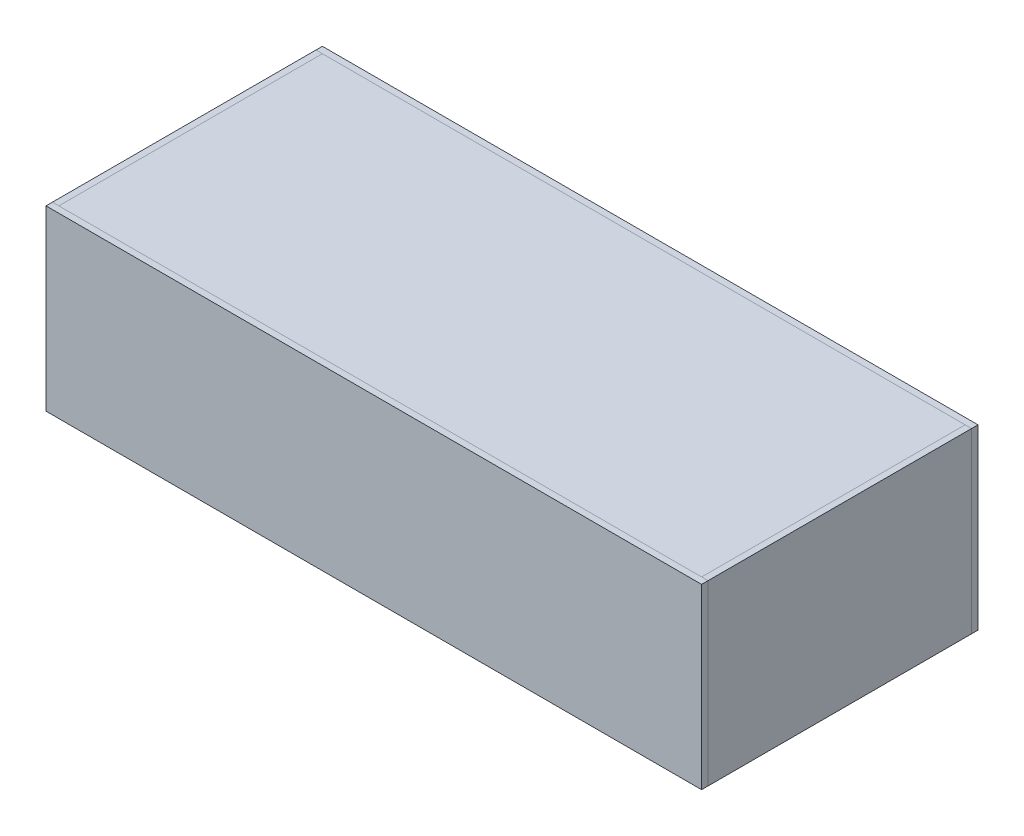
SolidWorks part; units mm, degrees
ref_plane "Plan de face" through (0, 0, 0) normal (0, 0, 1) x (1, 0, 0)
ref_plane "Plan de dessus" through (0, 0, 0) normal (0, 1, 0) x (1, 0, 0)
ref_plane "Plan de droite" through (0, 0, 0) normal (1, 0, 0) x (0, 0, -1)
sketch "Esquisse1" plane through (0, 0, 0) normal (0, 0, 1) x (1, 0, 0)
  line L1 (-714.5758, 139.7008) -> (815.4242, 139.7008)
  line L2 (-714.5758, 139.7008) -> (-714.5758, -275.2992)
  line L3 (-714.5758, -275.2992) -> (815.4242, -275.2992)
  line L4 (815.4242, 139.7008) -> (815.4242, -275.2992)
  dimension "D1" = 1530
  dimension "D2" = 415
extrude "Boss.-Extru.1" add sketch "Esquisse1" along normal blind 15
sketch "Esquisse2" plane through (0, 0, 15) normal (0, 0, 1) x (1, 0, 0)
  line L0 (-699.5758, 139.7008) -> (-699.5758, -275.2992)
  line L1 (815.4242, 139.7008) -> (-714.5758, 139.7008) construction
  line L2 (-714.5758, -275.2992) -> (815.4242, -275.2992) construction
  line L3 (-714.5758, 139.7008) -> (-714.5758, -275.2992) construction
  line L4 (800.4242, -275.2992) -> (800.4242, 139.7008)
  line L5 (815.4242, -275.2992) -> (815.4242, 139.7008) construction
  dimension "D1" = 15
  dimension "D2" = 15
extrude "Extru.-Mince1" add sketch "Esquisse2" along normal blind 615 separate body thin
sketch "Esquisse3" plane through (-699.5758, 0, 0) normal (1, 0, 0) x (0, 0, -1)
  line L0 (-630, 124.7008) -> (-15, 124.7008)
  line L1 (-630, 139.7008) -> (-630, -275.2992) construction
  line L2 (-15, 139.7008) -> (-15, -275.2992) construction
  line L3 (-630, 139.7008) -> (-15, 139.7008) construction
  dimension "D1" = 15
extrude "Extru.-Mince2" add sketch "Esquisse3" along normal blind 1500 separate body thin thin type one direction reverse wall 15
sketch "Esquisse5" plane through (-699.5758, 0, 0) normal (1, 0, 0) x (0, 0, -1)
  line L0 (-165, 24.7008) -> (-180, 24.7008)
  line L2 (-165, 24.7008) -> (-165, 124.7008)
  line L3 (-630, 124.7008) -> (-15, 124.7008) construction
  line L4 (-180, 24.7008) -> (-180, 124.7008)
  line L5 (-180, 124.7008) -> (-165, 124.7008)
  line L6 (-15, 139.7008) -> (-15, -275.2992) construction
  point P0 (-165, 74.7008)
  dimension "D1" = 100
  dimension "D2" = 15
  dimension "D3" = 150
extrude "Boss.-Extru.2" add sketch "Esquisse5" along normal blind 1500 separate body
sketch "Esquisse8" plane through (-699.5758, 0, 0) normal (1, 0, 0) x (0, 0, -1)
  line L5 (-630, 139.7008) -> (-630, -275.2992) construction
  line L6 (-180, 24.7008) -> (-630, 24.7008)
  line L7 (-180, 24.7008) -> (-180, 39.7008)
  line L8 (-180, 39.7008) -> (-630, 39.7008)
  line L9 (-630, 24.7008) -> (-630, 39.7008)
  dimension "D1" = 15
extrude "Boss.-Extru.3" add sketch "Esquisse8" along normal blind 1500 separate body
sketch "Esquisse9" plane through (-699.5758, 0, 0) normal (1, 0, 0) x (0, 0, -1)
  line L1 (-630, -275.2992) -> (-115, -275.2992)
  line L2 (-630, -275.2992) -> (-630, -260.2992)
  line L3 (-630, -260.2992) -> (-115, -260.2992)
  line L4 (-115, -275.2992) -> (-115, -260.2992)
  dimension "D1" = 15
  dimension "D2" = 515
extrude "Boss.-Extru.4" add sketch "Esquisse9" along normal blind 1500 separate body
sketch "Esquisse10" plane through (-699.5758, 0, 0) normal (1, 0, 0) x (0, 0, -1)
  line L5 (-115, -260.2992) -> (-130, -260.2992)
  line L6 (-115, -260.2992) -> (-115, 24.7008)
  line L7 (-115, 24.7008) -> (-130, 24.7008)
  line L8 (-130, -260.2992) -> (-130, 24.7008)
  dimension "D1" = 285
  dimension "D2" = 15
extrude "Boss.-Extru.5" add sketch "Esquisse10" along normal blind 1500 separate body
sketch "Esquisse12" plane through (0, 0, 115) normal (0, 0, -1) x (-1, 0, 0)
  line L0 (-800.4242, -275.2992) -> (699.5758, -275.2992) construction
  line L1 (207.0758, -275.2992) -> (192.0758, -275.2992)
  line L2 (207.0758, -275.2992) -> (207.0758, 24.7008)
  line L3 (207.0758, 24.7008) -> (192.0758, 24.7008)
  line L4 (192.0758, -275.2992) -> (192.0758, 24.7008)
  line L5 (-800.4242, 24.7008) -> (699.5758, 24.7008) construction
  line L6 (699.5758, -260.2992) -> (699.5758, 24.7008) construction
  line L7 (-800.4242, -260.2992) -> (699.5758, -260.2992) construction
  line L8 (-292.9242, -260.2992) -> (-307.9242, -260.2992)
  line L9 (-292.9242, -260.2992) -> (-292.9242, 24.7008)
  line L10 (-292.9242, 24.7008) -> (-307.9242, 24.7008)
  line L11 (-307.9242, -260.2992) -> (-307.9242, 24.7008)
  line L12 (-800.4242, -260.2992) -> (-800.4242, 24.7008) construction
  dimension "D1" = 15
  dimension "D2" = 492.5
  dimension "D3" = 15
  dimension "D4" = 492.5
extrude "Boss.-Extru.6" add sketch "Esquisse12" along normal blind 100 separate body
sketch "Esquisse13" plane through (0, -275.2992, 0) normal (0, -1, 0) x (1, 0, 0)
  line L0 (-699.5758, 630) -> (800.4242, 115) construction
  line L1 (800.4242, 630) -> (-699.5758, 115) construction
  line L2 (-424.5258, 630) -> (-424.5258, 115) construction
  line L3 (800.4242, 630) -> (-699.5758, 630) construction
  line L4 (800.4242, 115) -> (-699.5758, 115) construction
  line L5 (-699.5758, 630) -> (-699.5758, 15) construction
  line L6 (525.3742, 630) -> (525.3742, 115) construction
  line L7 (800.4242, 630) -> (800.4242, 15) construction
  circle A0 centre (50.4242, 372.5) radius 181.9
  circle A1 centre (-424.5258, 372.5) radius 181.9
  circle A2 centre (525.3742, 372.5) radius 181.9
  dimension "D3" = 363.8
  dimension "D4" = 363.8
  dimension "D5" = 363.8
  dimension "D1" = 275.05
  dimension "D2" = 275.05
extrude "Enlèv. mat.-Extru.1" cut sketch "Esquisse13" against normal blind 15
sketch "Esquisse14" plane through (0, 0, 630) normal (0, 0, 1) x (1, 0, 0)
  line L1 (-714.5758, -275.2992) -> (815.4242, -275.2992)
  line L2 (-714.5758, -275.2992) -> (-714.5758, 139.7008)
  line L3 (-714.5758, 139.7008) -> (815.4242, 139.7008)
  line L4 (815.4242, -275.2992) -> (815.4242, 139.7008)
extrude "Boss.-Extru.7" add sketch "Esquisse14" along normal blind 15 separate body
sketch "Esquisse16" plane through (-699.5758, 0, 0) normal (1, 0, 0) x (0, 0, -1)
  line L0 (-180, 39.7008) -> (-630, 39.7008) construction
  line L5 (-412.5, 39.7008) -> (-397.5, 39.7008)
  line L6 (-412.5, 39.7008) -> (-412.5, 124.7008)
  line L7 (-412.5, 124.7008) -> (-397.5, 124.7008)
  line L12 (-397.5, 39.7008) -> (-397.5, 124.7008)
  line L13 (-180, 124.7008) -> (-180, 24.7008) construction
  dimension "D1" = 15
  dimension "D2" = 85
  dimension "D3" = 217.5
extrude "Boss.-Extru.8" add sketch "Esquisse16" along normal blind 1500 separate body
